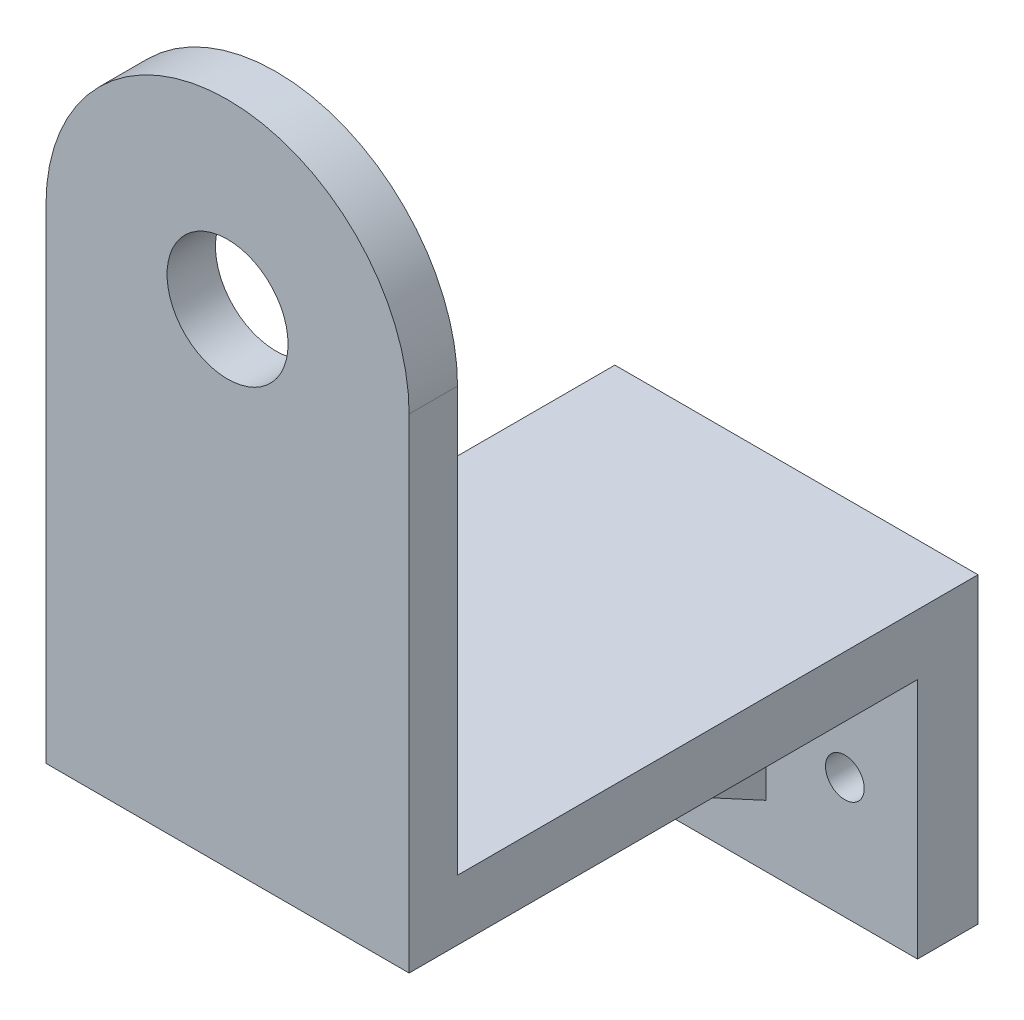
SolidWorks part; units mm, degrees
material "PEI"
ref_plane "Front Plane" through (0, 0, 0) normal (0, 0, 1) x (1, 0, 0)
ref_plane "Top Plane" through (0, 0, 0) normal (0, 1, 0) x (1, 0, 0)
ref_plane "Right Plane" through (0, 0, 0) normal (1, 0, 0) x (0, 0, -1)
sketch "Sketch1" plane through (0, 0, 0) normal (0, 0, 1) x (1, 0, 0)
  line L0 (15, 0) -> (15, -40)
  line L1 (15, -40) -> (-15, -40)
  line L2 (-15, -40) -> (-15, 0)
  arc A0 (15, 0) -> (-15, 0) centre (0, 0) ccw
  circle A1 centre (0, 0) radius 5
  dimension "D1" = 30
  dimension "D2" = 10
  dimension "D3" = 40
extrude "Boss-Extrude1" add sketch "Sketch1" along normal blind 4
sketch "Sketch2" plane through (0, -40, 0) normal (0, -1, 0) x (1, 0, 0)
  line L0 (15, 4) -> (15, 0) construction
  line L1 (-15, 0) -> (15, 0)
  line L2 (-15, 0) -> (-15, -38)
  line L3 (-15, -38) -> (15, -38)
  line L4 (15, 0) -> (15, -38)
  line L5 (-15, 0) -> (15, -38) construction
  line L6 (-15, -38) -> (15, 0) construction
  point P4 (0, -19)
  dimension "D1" = 38
extrude "Boss-Extrude2" add sketch "Sketch2" against normal blind 5
sketch "Sketch4" plane through (0, 0, -38) normal (0, 0, -1) x (-1, 0, 0)
  line L0 (15, -35) -> (15, -40) construction
  line L2 (-15, -35) -> (-15, -60)
  line L3 (-15, -60) -> (15, -60)
  line L4 (15, -35) -> (15, -60)
  line L5 (-15, -35) -> (15, -60) construction
  line L6 (-15, -60) -> (15, -35) construction
  line L7 (-15, -35) -> (15, -35)
  line L8 (15, -40) -> (-15, -40) construction
  circle A0 centre (9, -50) radius 1.6
  circle A1 centre (-9, -50) radius 1.6
  circle A2 centre (0, -53) radius 1.6 construction
  point P4 (0, -47.5)
  point P17 (0, -60)
  dimension "D2" = 3.2
  dimension "D1" = 20
  dimension "D3" = 9
  dimension "D4" = 18
  dimension "D5" = 10
  dimension "D6" = 7
extrude "Boss-Extrude3" add sketch "Sketch4" along normal blind 5
sketch "Sketch5" plane through (0, 0, 0) normal (1, 0, 0) x (0, 0, -1)
  line L0 (38, -54.892) -> (10.4067, -40)
  line L1 (38, -40) -> (38, -60) construction
  line L3 (-4, -40) -> (38, -40) construction
rib "Rib1" sketch "Sketch5" sketch "Sketch5" thickness 5 extrusion direction parallel to sketch draft on no parameters "D1"=5
